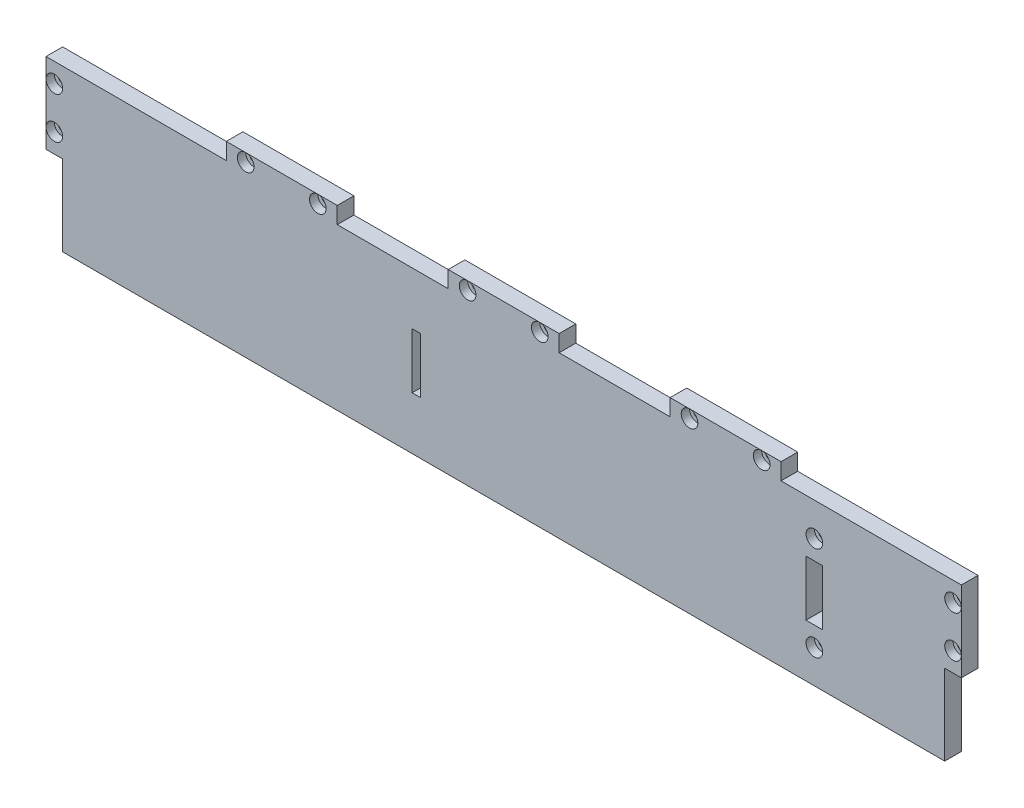
SolidWorks part; units mm, degrees
ref_plane "Plan de face" through (0, 0, 0) normal (0, 0, 1) x (1, 0, 0)
ref_plane "Plan de dessus" through (0, 0, 0) normal (0, 1, 0) x (1, 0, 0)
ref_plane "Plan de droite" through (0, 0, 0) normal (1, 0, 0) x (0, 0, -1)
sketch "Esquisse1" plane through (0, 0, 0) normal (0, 0, 1) x (1, 0, 0)
  line L1 (0, 0) -> (-330, 0)
  line L2 (0, 0) -> (0, 64)
  line L3 (0, 64) -> (-330, 64)
  line L4 (-330, 0) -> (-330, 64)
  dimension "D1" = 64
  dimension "D2" = 330
extrude "Boss.-Extru.1" add sketch "Esquisse1" along normal blind 6
sketch "Esquisse2" plane through (0, 0, 6) normal (0, 0, 1) x (1, 0, 0)
  line L0 (0, 64) -> (-330, 64) construction
  line L1 (-330, 64) -> (-265, 64)
  line L2 (-330, 64) -> (-330, 58)
  line L3 (-330, 58) -> (-265, 58)
  line L4 (-265, 64) -> (-265, 58)
  line L5 (-225, 64) -> (-185, 64)
  line L6 (-225, 64) -> (-225, 58)
  line L7 (-225, 58) -> (-185, 58)
  line L8 (-185, 64) -> (-185, 58)
  line L10 (-145, 64) -> (-105, 64)
  line L11 (-145, 64) -> (-145, 58)
  line L12 (-145, 58) -> (-105, 58)
  line L13 (-105, 64) -> (-105, 58)
  line L14 (0, 64) -> (-65, 64)
  line L15 (0, 64) -> (0, 58)
  line L16 (0, 58) -> (-65, 58)
  line L17 (-65, 64) -> (-65, 58)
  line L18 (-330, 0) -> (-324, 0)
  line L19 (-330, 0) -> (-330, 29)
  line L20 (-330, 29) -> (-324, 29)
  line L21 (-324, 0) -> (-324, 29)
  line L22 (0, 0) -> (-6, 0)
  line L23 (0, 0) -> (0, 29)
  line L24 (0, 29) -> (-6, 29)
  line L25 (-6, 0) -> (-6, 29)
  dimension "D1" = 6
  dimension "D2" = 6
  dimension "D3" = 6
  dimension "D4" = 6
  dimension "D5" = 65
  dimension "D6" = 40
  dimension "D7" = 40
  dimension "D8" = 65
  dimension "D9" = 40
  dimension "D10" = 40
  dimension "D11" = 29
  dimension "D12" = 6
  dimension "D13" = 29
  dimension "D14" = 6
extrude "Enlèv. mat.-Extru.1" cut sketch "Esquisse2" against normal through all
sketch "Esquisse3" plane through (0, 0, 6) normal (0, 0, 1) x (1, 0, 0)
  line L0 (-330, 58) -> (-330, 29) construction
  line L1 (-198, 39) -> (-195, 39)
  line L2 (-198, 39) -> (-198, 19)
  line L3 (-198, 19) -> (-195, 19)
  line L4 (-195, 39) -> (-195, 19)
  line L5 (-56, 39) -> (-50, 39)
  line L6 (-56, 39) -> (-56, 19)
  line L7 (-56, 19) -> (-50, 19)
  line L8 (-50, 39) -> (-50, 19)
  line L9 (-225, 58) -> (-185, 58) construction
  line L11 (0, 29) -> (0, 58) construction
  line L12 (-65, 58) -> (0, 58) construction
  dimension "D1" = 3
  dimension "D2" = 20
  dimension "D3" = 6
  dimension "D4" = 20
  dimension "D5" = 132
  dimension "D6" = 19
  dimension "D7" = 50
  dimension "D8" = 19
extrude "Enlèv. mat.-Extru.2" cut sketch "Esquisse3" against normal through all
sketch "Esquisse4" plane through (0, 0, 6) normal (0, 0, 1) x (1, 0, 0)
  line L0 (-330, 58) -> (-265, 58) construction
  line L1 (-330, 58) -> (-330, 29) construction
  line L4 (-265, 58) -> (-265, 64) construction
  line L5 (-225, 64) -> (-265, 64) construction
  line L6 (-225, 64) -> (-225, 58) construction
  line L7 (-185, 58) -> (-185, 64) construction
  line L8 (-145, 64) -> (-185, 64) construction
  line L9 (-145, 64) -> (-145, 58) construction
  line L10 (-105, 58) -> (-105, 64) construction
  line L11 (-65, 64) -> (-105, 64) construction
  line L12 (-65, 64) -> (-65, 58) construction
  line L13 (-65, 58) -> (0, 58) construction
  line L14 (0, 29) -> (0, 58) construction
  line L15 (-50, 39) -> (-56, 39) construction
  line L16 (-50, 19) -> (-50, 39) construction
  line L17 (-56, 39) -> (-56, 19) construction
  line L18 (-56, 19) -> (-50, 19) construction
  line L20 (-330, 58) -> (-330, 29) construction
  line L21 (-324, 29) -> (-330, 29) construction
  line L22 (0, 29) -> (0, 58) construction
  line L23 (0, 29) -> (-6, 29) construction
  circle A0 centre (-327, 51) radius 1.5
  circle A1 centre (-327, 36) radius 1.5
  circle A2 centre (-3, 36) radius 1.5
  circle A3 centre (-258, 61) radius 1.5
  circle A4 centre (-232, 61) radius 1.5
  circle A5 centre (-178, 61) radius 1.5
  circle A6 centre (-152, 61) radius 1.5
  circle A7 centre (-98, 61) radius 1.5
  circle A8 centre (-72, 61) radius 1.5
  circle A9 centre (-53, 46) radius 1.5
  circle A10 centre (-53, 12) radius 1.5
  circle A13 centre (-3, 51) radius 1.5
  point P52 (-145, 61)
  dimension "D1" = 3
  dimension "D2" = 7
  dimension "D3" = 3
  dimension "D5" = 3
  dimension "D6" = 3
  dimension "D7" = 7
  dimension "D8" = 3
  dimension "D9" = 3
  dimension "D10" = 3
  dimension "D11" = 7
  dimension "D12" = 3
  dimension "D13" = 3
  dimension "D14" = 3
  dimension "D15" = 7
  dimension "D16" = 3
  dimension "D17" = 7
  dimension "D18" = 3
  dimension "D19" = 3
  dimension "D20" = 3
  dimension "D21" = 7
  dimension "D22" = 3
  dimension "D23" = 3
  dimension "D24" = 7
  dimension "D25" = 3
  dimension "D26" = 7
  dimension "D27" = 3
  dimension "D28" = 3
  dimension "D29" = 7
  dimension "D30" = 3
  dimension "D31" = 7
  dimension "D37" = 3
  dimension "D38" = 7
  dimension "D39" = 3
  dimension "D40" = 3
  dimension "D41" = 3
  dimension "D42" = 7
extrude "Enlèv. mat.-Extru.3" cut sketch "Esquisse4" against normal through all
sketch "Esquisse5" plane through (0, 0, 6) normal (0, 0, 1) x (1, 0, 0)
  circle A0 centre (-3, 36) radius 2.995
  circle A1 centre (-327, 36) radius 2.995
  circle A2 centre (-327, 51) radius 2.995
  circle A3 centre (-258, 61) radius 2.995
  circle A4 centre (-232, 61) radius 2.995
  circle A6 centre (-178, 61) radius 2.995
  circle A7 centre (-152, 61) radius 2.995
  circle A8 centre (-98, 61) radius 2.995
  circle A9 centre (-72, 61) radius 2.995
  circle A10 centre (-53, 46) radius 2.995
  circle A11 centre (-53, 12) radius 2.995
  circle A14 centre (-3, 51) radius 2.995
  dimension "D1" = 5.99
  dimension "D2" = 5.99
  dimension "D3" = 5.99
  dimension "D4" = 5.99
  dimension "D5" = 5.99
  dimension "D6" = 5.99
  dimension "D7" = 5.99
  dimension "D8" = 5.99
  dimension "D9" = 5.99
  dimension "D11" = 5.99
  dimension "D12" = 5.99
  dimension "D13" = 5.99
extrude "Enlèv. mat.-Extru.4" cut sketch "Esquisse5" against normal blind 3
